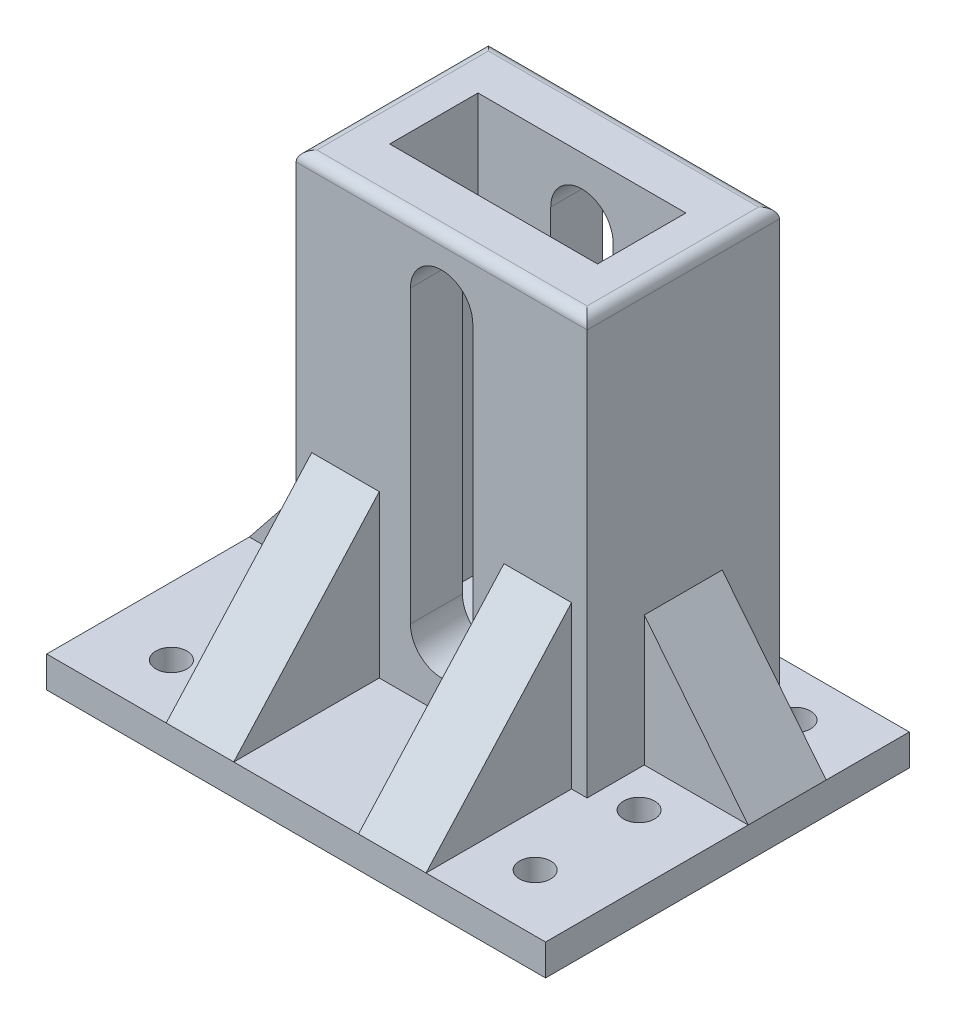
SolidWorks part; units mm, degrees
ref_plane "前视基准面" through (0, 0, 0) normal (0, 0, 1) x (1, 0, 0)
ref_plane "上视基准面" through (0, 0, 0) normal (0, 1, 0) x (1, 0, 0)
ref_plane "右视基准面" through (0, 0, 0) normal (1, 0, 0) x (0, 0, -1)
other "Configuration Table"
sketch "草图1" plane through (0, 0, 0) normal (0, 1, 0) x (1, 0, 0)
  line L0 (-13.1497, 50.7938) -> (-13.1497, -28.9315) construction
  line L1 (-61.1497, 43.7897) -> (34.8503, 43.7897)
  line L5 (-48.1497, 43.7897) -> (21.8503, 43.7897)
  line L6 (-48.1497, 43.7897) -> (-48.1497, -28.9315) construction
  line L8 (21.8503, 43.7897) -> (21.8503, -28.9315) construction
  line L10 (-61.1497, 43.7897) -> (34.8503, 43.7897)
  line L11 (-61.1497, 43.7897) -> (-61.1497, -26.2103)
  line L12 (-61.1497, -26.2103) -> (34.8503, -26.2103)
  line L13 (34.8503, 43.7897) -> (34.8503, -26.2103)
  circle A0 centre (-48.1497, 34.7897) radius 3
  circle A1 centre (21.8503, 34.7897) radius 3
  circle A2 centre (-48.1497, -15.2103) radius 3
  circle A3 centre (21.8503, -15.2103) radius 3
  circle A4 centre (-48.1497, 4.7897) radius 3
  circle A5 centre (21.8503, 4.7897) radius 3
  dimension "D4" = 9
  dimension "D5" = 9
  dimension "D6" = 50
  dimension "D7" = 50
  dimension "D8" = 35
  dimension "D10" = 20
  dimension "D11" = 20
  dimension "D12" = 6
  dimension "D13" = 6
  dimension "D14" = 6
  dimension "D15" = 6
  dimension "D16" = 6
  dimension "6" = 6
  dimension "D1" = 48
  dimension "D2" = 48
  dimension "D3" = 70
  dimension "D9" = 35
extrude "凸台-拉伸1" add sketch "草图1" along normal blind 6 contours L13 L1 L11 L12 A5 A4 A3 A2 A1 A0
sketch "草图2" plane through (0, 6, 0) normal (0, 1, 0) x (1, 0, 0)
  line L0 (-13.1497, 47.7191) -> (-13.1497, -35.4795) construction
  line L1 (-61.1497, 43.7897) -> (-61.1497, -26.2103) construction
  line L2 (-61.1497, 43.7897) -> (34.8503, 43.7897) construction
  line L3 (-33.1497, 28.7897) -> (6.8503, 28.7897)
  line L4 (-33.1497, 28.7897) -> (-33.1497, 11.7897)
  line L5 (-33.1497, 11.7897) -> (6.8503, 11.7897)
  line L6 (6.8503, 28.7897) -> (6.8503, 11.7897)
  line L7 (-33.1497, 28.7897) -> (6.8503, 11.7897) construction
  line L8 (-33.1497, 11.7897) -> (6.8503, 28.7897) construction
  line L9 (34.8503, 43.7897) -> (34.8503, -26.2103) construction
  line L11 (-41.1497, 38.7897) -> (14.8503, 38.7897)
  line L12 (-41.1497, 38.7897) -> (-41.1497, 1.7897)
  line L13 (-41.1497, 1.7897) -> (14.8503, 1.7897)
  line L14 (14.8503, 38.7897) -> (14.8503, 1.7897)
  line L15 (-41.1497, 38.7897) -> (14.8503, 1.7897) construction
  line L16 (-41.1497, 1.7897) -> (14.8503, 38.7897) construction
  point P4 (-13.1497, 20.2897)
  point P13 (-13.1497, 20.2897)
  dimension "D1" = 48
  dimension "D2" = 40
  dimension "D3" = 17
  dimension "D4" = 15
  dimension "D5" = 48
  dimension "D6" = 10
  dimension "D7" = 8
extrude "凸台-拉伸2" add sketch "草图2" along normal blind 80
sketch "草图3" plane through (14.8503, 0, 0) normal (1, 0, 0) x (0, 0, -1)
  line L0 (20.2897, 86) -> (20.2897, -3.5497) construction
  line L1 (1.7897, 86) -> (38.7897, 86) construction
sketch "草图4" plane through (-41.1497, 0, 0) normal (-1, 0, 0) x (0, 0, 1)
  line L0 (-20.2897, 86) -> (-20.2897, -3.5497) construction
ref_plane "基准面1" through (0, 0, -20.2897) normal (0, 0, 1) x (1, 0, 0)
sketch "草图5" plane through (0, 0, -20.2897) normal (0, 0, 1) x (1, 0, 0)
  line L0 (-61.1497, 6) -> (-41.1497, 31)
  line L1 (-41.1497, 86) -> (-41.1497, -3.5497) construction
  line L2 (-41.1497, 31) -> (-41.1497, 6)
  line L3 (-41.1497, 6) -> (-61.1497, 6)
  line L4 (14.8503, 31) -> (34.8503, 6)
  line L5 (14.8503, 86) -> (14.8503, -3.5497) construction
  line L6 (34.8503, 6) -> (14.8503, 6)
  line L7 (14.8503, 31) -> (14.8503, 6)
  dimension "D1" = 25
  dimension "D2" = 25
extrude "凸台-拉伸3" add sketch "草图5" along normal mid plane 15
sketch "草图6" plane through (0, 0, -1.7897) normal (0, 0, 1) x (1, 0, 0)
  line L0 (-13.1497, 86) -> (-13.1497, -11.8788) construction
  line L1 (-41.1497, 86) -> (14.8503, 86) construction
sketch "草图7" plane through (0, 0, -38.7897) normal (0, 0, -1) x (-1, 0, 0)
  line L0 (13.1497, 86) -> (13.1497, -11.8788) construction
  line L1 (-14.8503, 86) -> (41.1497, 86) construction
ref_plane "基准面2" through (-13.1497, 0, 0) normal (1, 0, 0) x (0, 0, -1)
sketch "草图8" plane through (-13.1497, 0, 0) normal (1, 0, 0) x (0, 0, -1)
  line L0 (-26.2103, 6) -> (1.7897, 37.0606)
  line L1 (1.7897, 86) -> (1.7897, -11.8788) construction
  line L2 (1.7897, 37.0606) -> (1.7897, 6)
  line L3 (1.7897, 6) -> (-26.2103, 6)
extrude "凸台-拉伸4" add sketch "草图8" along normal mid plane 50
sketch "草图9" plane through (0, 0, -38.7897) normal (0, 0, -1) x (-1, 0, 0)
  line L0 (13.1497, 74) -> (13.1497, 18) construction
  line L1 (13.1497, 86) -> (13.1497, -11.8788) construction
  line L2 (19.1497, 74) -> (19.1497, 18)
  line L3 (7.1497, 74) -> (7.1497, 18)
  line L4 (-14.8503, 86) -> (41.1497, 86) construction
  line L5 (-14.8503, 6) -> (41.1497, 6) construction
  arc A0 (19.1497, 74) -> (7.1497, 74) centre (13.1497, 74) ccw
  arc A1 (7.1497, 18) -> (19.1497, 18) centre (13.1497, 18) ccw
  point P4 (13.1497, 46)
  dimension "D3" = 12
  dimension "D1" = 12
  dimension "D2" = 12
extrude "切除-拉伸1" cut sketch "草图9" against normal through all
sketch "草图10" plane through (0, 86, 0) normal (0, 1, 0) x (1, 0, 0)
  line L0 (-19.1497, 1.7897) -> (-38.1497, 1.7897) construction
  line L1 (-25.1497, 1.7897) -> (-1.1497, 1.7897)
  line L2 (-25.1497, 1.7897) -> (-25.1497, -29.1186)
  line L3 (-25.1497, -29.1186) -> (-1.1497, -29.1186)
  line L4 (-1.1497, 1.7897) -> (-1.1497, -29.1186)
  line L5 (-13.1497, -20.35) -> (-13.1497, 20.35) construction
  dimension "D1" = 12
  dimension "D2" = 24
extrude "切除-拉伸2" cut sketch "草图10" against normal up to surface (80 mm away) up to face at (20.5169, 6, 3.8769)
fillet "圆角1" radius 2 4 edges at (-13.1497, 86, -38.7897) (14.8503, 86, -20.2897) (-41.1497, 86, -20.2897) (-13.1497, 86, -1.7897)
